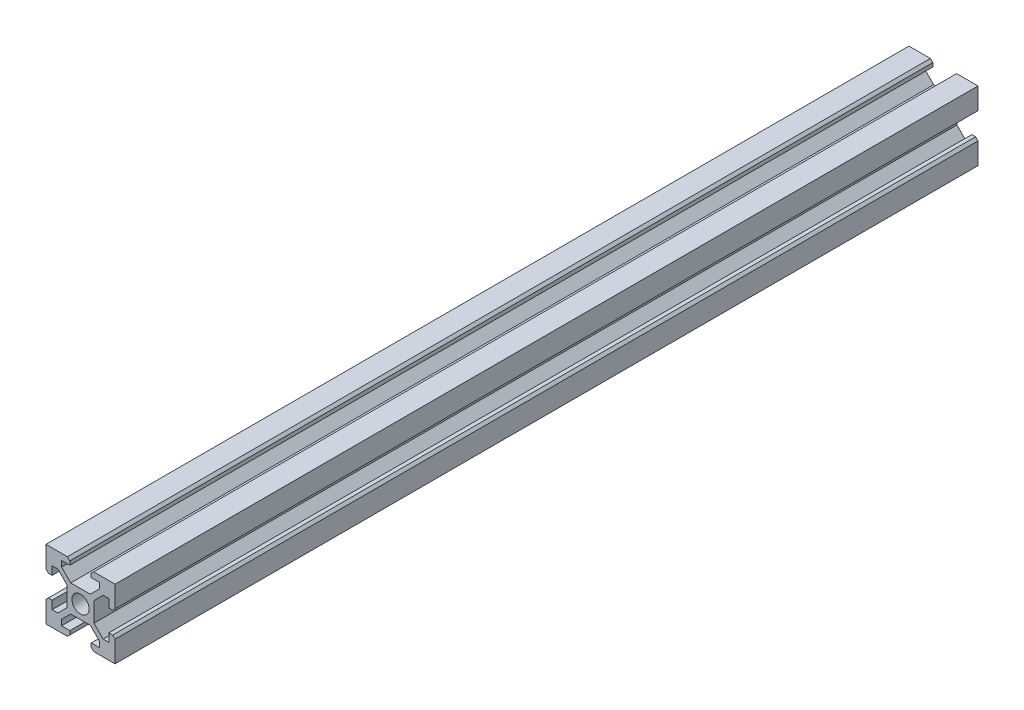
SolidWorks part; units mm, degrees
material "1060 Alloy"
ref_plane "Front Plane" through (0, 0, 0) normal (0, 0, 1) x (1, 0, 0)
ref_plane "Top Plane" through (0, 0, 0) normal (0, 1, 0) x (1, 0, 0)
ref_plane "Right Plane" through (0, 0, 0) normal (1, 0, 0) x (0, 0, -1)
sketch "Sketch1" plane through (0, 0, 0) normal (0, 0, 1) x (1, 0, 0)
  line L0 (3.9, -2.8393) -> (6.5607, -5.5)
  line L1 (-10, 10) -> (10, 10) construction
  line L2 (-10, 10) -> (-10, -10) construction
  line L3 (-10, -10) -> (10, -10) construction
  line L4 (10, 10) -> (10, -10) construction
  line L5 (-10, 10) -> (10, -10) construction
  line L6 (-10, -10) -> (10, 10) construction
  line L7 (-3.9, -3.9) -> (3.9, -3.9) construction
  line L8 (-3.9, -3.9) -> (-3.9, 3.9) construction
  line L9 (-3.9, 3.9) -> (3.9, 3.9) construction
  line L10 (3.9, -3.9) -> (3.9, 3.9) construction
  line L11 (-3.9, -3.9) -> (3.9, 3.9) construction
  line L12 (-3.9, 3.9) -> (3.9, -3.9) construction
  line L13 (-10, 10) -> (-5.5, 10) construction
  line L14 (-10, 10) -> (-10, 5.5) construction
  line L15 (-10, 5.5) -> (-5.5, 5.5) construction
  line L16 (-5.5, 10) -> (-5.5, 5.5) construction
  line L17 (10, 10) -> (5.5, 10) construction
  line L18 (10, 10) -> (10, 5.5) construction
  line L19 (10, 5.5) -> (5.5, 5.5) construction
  line L20 (5.5, 10) -> (5.5, 5.5) construction
  line L21 (-10, -10) -> (-5.5, -10) construction
  line L22 (-10, -10) -> (-10, -5.5) construction
  line L23 (-10, -5.5) -> (-5.5, -5.5) construction
  line L24 (-5.5, -10) -> (-5.5, -5.5) construction
  line L25 (10, -10) -> (5.5, -10) construction
  line L26 (10, -10) -> (10, -5.5) construction
  line L27 (10, -5.5) -> (5.5, -5.5) construction
  line L28 (5.5, -10) -> (5.5, -5.5) construction
  line L29 (2.8393, -3.9) -> (5.5, -6.5607)
  line L30 (-5.5, 6.5607) -> (-2.8393, 3.9)
  line L31 (-6.5607, 5.5) -> (-3.9, 2.8393)
  line L32 (5.5, 6.5607) -> (2.8393, 3.9)
  line L33 (6.5607, 5.5) -> (3.9, 2.8393)
  line L34 (-6.5607, -5.5) -> (-3.9, -2.8393)
  line L35 (-5.5, -6.5607) -> (-2.8393, -3.9)
  line L36 (-2.8393, 3.9) -> (2.8393, 3.9)
  line L37 (-3.9, 2.8393) -> (-3.9, -2.8393)
  line L38 (-2.8393, -3.9) -> (2.8393, -3.9)
  line L39 (3.9, -2.8393) -> (3.9, 2.8393)
  line L40 (5.5, 6.5607) -> (5.5, 8.2007)
  line L41 (5.5, 8.2007) -> (3.1, 8.2007)
  line L42 (3.1, 8.2007) -> (3.1, 9.3)
  line L43 (3.1, 9.3) -> (3.8, 10)
  line L44 (3.8, 10) -> (10, 10)
  line L45 (10, 10) -> (10, 3.8)
  line L46 (10, 3.8) -> (9.3, 3.1)
  line L47 (9.3, 3.1) -> (8.2007, 3.1)
  line L48 (8.2007, 3.1) -> (8.2007, 5.5)
  line L49 (8.2007, 5.5) -> (6.5607, 5.5)
  line L50 (3.1, -8.2007) -> (5.5, -8.2007)
  line L51 (3.1, -9.3) -> (3.1, -8.2007)
  line L52 (3.8, -10) -> (3.1, -9.3)
  line L53 (10, -10) -> (3.8, -10)
  line L54 (10, -3.8) -> (10, -10)
  line L55 (9.3, -3.1) -> (10, -3.8)
  line L56 (8.2007, -3.1) -> (9.3, -3.1)
  line L57 (8.2007, -5.5) -> (8.2007, -3.1)
  line L58 (6.5607, -5.5) -> (8.2007, -5.5)
  line L59 (5.5, -8.2007) -> (5.5, -6.5607)
  line L60 (-8.2007, -3.1) -> (-8.2007, -5.5)
  line L61 (-9.3, -3.1) -> (-8.2007, -3.1)
  line L62 (-10, -3.8) -> (-9.3, -3.1)
  line L63 (-10, -10) -> (-10, -3.8)
  line L64 (-3.8, -10) -> (-10, -10)
  line L65 (-3.1, -9.3) -> (-3.8, -10)
  line L66 (-3.1, -8.2007) -> (-3.1, -9.3)
  line L67 (-5.5, -8.2007) -> (-3.1, -8.2007)
  line L68 (-5.5, -6.5607) -> (-5.5, -8.2007)
  line L69 (-8.2007, -5.5) -> (-6.5607, -5.5)
  line L70 (-3.1, 8.2007) -> (-5.5, 8.2007)
  line L71 (-3.1, 9.3) -> (-3.1, 8.2007)
  line L72 (-3.8, 10) -> (-3.1, 9.3)
  line L73 (-10, 10) -> (-3.8, 10)
  line L74 (-10, 3.8) -> (-10, 10)
  line L75 (-9.3, 3.1) -> (-10, 3.8)
  line L76 (-8.2007, 3.1) -> (-9.3, 3.1)
  line L77 (-8.2007, 5.5) -> (-8.2007, 3.1)
  line L78 (-6.5607, 5.5) -> (-8.2007, 5.5)
  line L79 (-5.5, 8.2007) -> (-5.5, 6.5607)
  circle A0 centre (0, 0) radius 2.5
  point P83 (0, 0)
  dimension "D1" = 5
  dimension "D2" = 20
  dimension "D3" = 7.8
  dimension "D4" = 4.5
  dimension "D5" = 1.5
  dimension "D6" = 0.75
  dimension "D7" = 1.5
  dimension "D8" = 0.75
  dimension "D9" = 1.5
  dimension "D10" = 0.75
  dimension "D11" = 1.5
  dimension "D12" = 0.75
  dimension "D13" = 1.64
  dimension "D14" = 45
  dimension "D15" = 3.1
  dimension "D16" = 6.2
  dimension "D17" = 6.2
  dimension "D18" = 3.1
  dimension "D19" = 4
extrude "Boss-Extrude1" add sketch "Sketch1" along normal mid plane 250 contours L79 L70 L71 L72 L73 L74 L75 L76 L77 L78 L31 L37 L34 L69 L60 L61 L62 L63 L64 L65 L66 L67 L68 L35 L38 L29 L59 L50 L51 L52 L53 L54 L55 L56 L57 L58 L0 L39 L33 L49 L48 L47 L46 L45 L44 L43 L42 L41 L40 L32 L36
